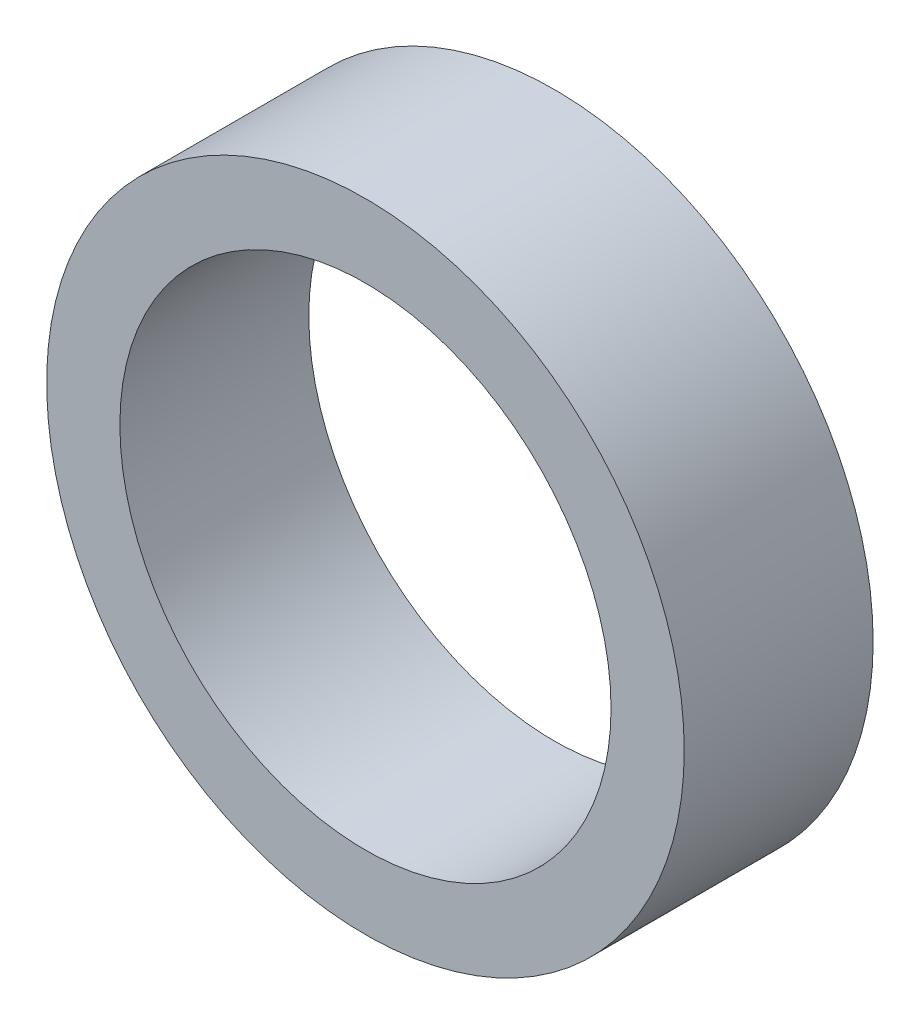
SolidWorks part; units mm, degrees
ref_plane "前视基准面" through (0, 0, 0) normal (0, 0, 1) x (1, 0, 0)
ref_plane "上视基准面" through (0, 0, 0) normal (0, 1, 0) x (1, 0, 0)
ref_plane "右视基准面" through (0, 0, 0) normal (1, 0, 0) x (0, 0, -1)
sketch "草图1" plane through (0, 0, 0) normal (0, 0, 1) x (1, 0, 0)
  circle A0 centre (0, 0) radius 6.75
  circle A1 centre (0, 0) radius 5.2
  dimension "D1" = 10.4
  dimension "D2" = 13.5
extrude "凸台-拉伸1" add sketch "草图1" along normal blind 4
